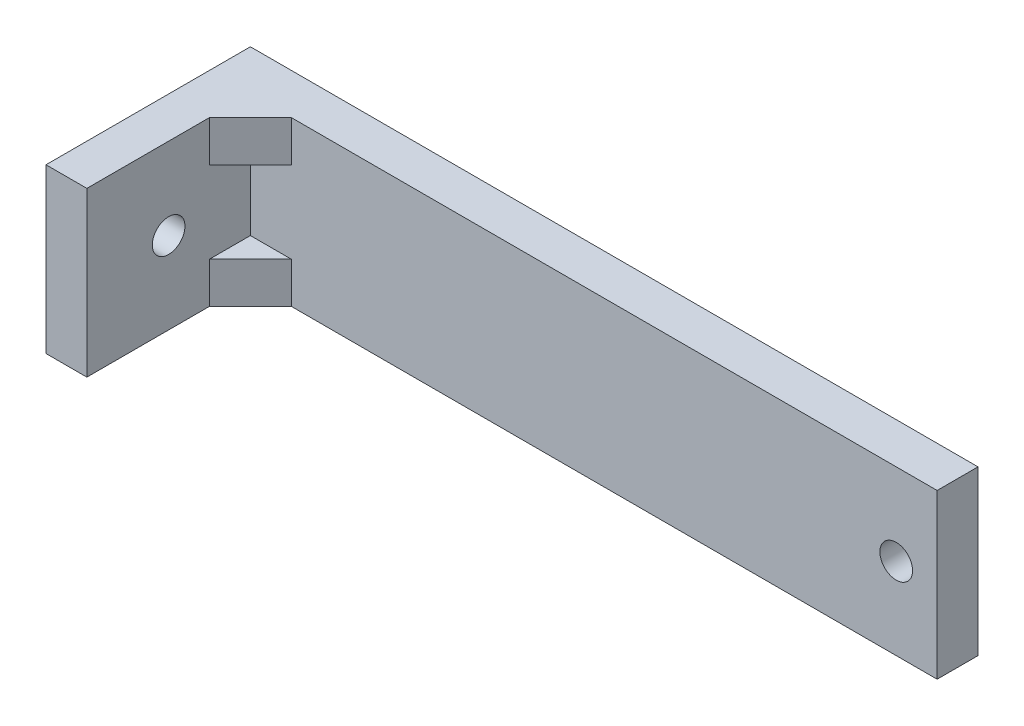
SolidWorks part; units mm, degrees
ref_plane "Front Plane" through (0, 0, 0) normal (0, 0, 1) x (1, 0, 0)
ref_plane "Top Plane" through (0, 0, 0) normal (0, 1, 0) x (1, 0, 0)
ref_plane "Right Plane" through (0, 0, 0) normal (1, 0, 0) x (0, 0, -1)
sketch "Sketch1" plane through (0, 0, 0) normal (0, 0, 1) x (1, 0, 0)
  line L1 (-44.5, 10) -> (44.5, 10)
  line L2 (-44.5, 10) -> (-44.5, -10)
  line L3 (-44.5, -10) -> (44.5, -10)
  line L4 (44.5, 10) -> (44.5, -10)
  line L5 (-44.5, 10) -> (44.5, -10) construction
  line L6 (-44.5, -10) -> (44.5, 10) construction
  point P0 (0, 0)
  dimension "D1" = 89
  dimension "D2" = 20
extrude "Boss-Extrude1" add sketch "Sketch1" along normal blind 5
sketch "Sketch2" plane through (0, 0, 5) normal (0, 0, 1) x (1, 0, 0)
  line L0 (-44.5, -10) -> (44.5, -10) construction
  line L1 (-44.5, 10) -> (-39.5, 10)
  line L2 (-44.5, 10) -> (-44.5, -10)
  line L3 (-44.5, -10) -> (-39.5, -10)
  line L4 (-39.5, 10) -> (-39.5, -10)
  dimension "D1" = 5
extrude "Boss-Extrude2" add sketch "Sketch2" along normal blind 20
sketch "Sketch3" plane through (-39.5, 0, 0) normal (1, 0, 0) x (0, 0, -1)
  line L0 (-25, -10) -> (-25, 10) construction
  line L1 (-25, -10) -> (-5, -10) construction
  circle A0 centre (-15, 0) radius 2
  dimension "D1" = 4
  dimension "D3" = 10
  dimension "D2" = 10
extrude "Cut-Extrude1" cut sketch "Sketch3" against normal through all
sketch "Sketch4" plane through (0, 0, 0) normal (0, 0, -1) x (-1, 0, 0)
  line L0 (44.5, 10) -> (44.5, -10) construction
  circle A0 centre (-39.5, 0) radius 2
  dimension "D1" = 4
  dimension "D2" = 84
extrude "Cut-Extrude2" cut sketch "Sketch4" against normal blind 20
sketch "Sketch5" plane through (-39.5, 0, 0) normal (1, 0, 0) x (0, 0, -1)
  line L1 (-5, -10) -> (-10, -10)
  line L2 (-5, -10) -> (-5, -5)
  line L3 (-5, -5) -> (-10, -5)
  line L4 (-10, -10) -> (-10, -5)
  line L5 (-5, 10) -> (-10, 10)
  line L6 (-5, 10) -> (-5, 5)
  line L7 (-5, 5) -> (-10, 5)
  line L8 (-10, 10) -> (-10, 5)
  dimension "D1" = 5
  dimension "D2" = 5
  dimension "D3" = 5
  dimension "D4" = 5
extrude "Boss-Extrude3" add sketch "Sketch5" along normal blind 5
sketch "Sketch6" plane through (0, 10, 0) normal (0, 1, 0) x (1, 0, 0)
  line L0 (-34.5, -5) -> (-39.5, -10)
  line L1 (-39.5, -10) -> (-34.5, -10)
  line L2 (-34.5, -10) -> (-34.5, -5)
extrude "Cut-Extrude3" cut sketch "Sketch6" against normal through all
